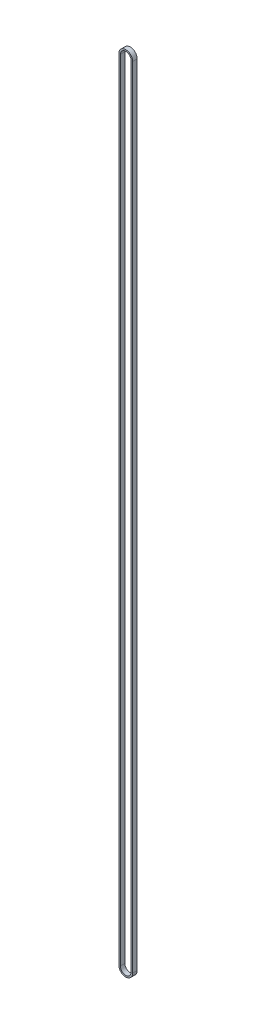
SolidWorks part; units mm, degrees
ref_plane "Front Plane" through (0, 0, 0) normal (0, 0, 1) x (1, 0, 0)
ref_plane "Top Plane" through (0, 0, 0) normal (0, 1, 0) x (1, 0, 0)
ref_plane "Right Plane" through (0, 0, 0) normal (1, 0, 0) x (0, 0, -1)
sketch "Sketch2" plane through (0, 0, 0) normal (0, 0, 1) x (1, 0, 0)
  line L0 (0, 0) -> (1, 0) construction
  line L1 (0, 0) -> (0, 1) construction
  line L2 (7.11, 0) -> (7.11, -1041)
  line L3 (-7.11, -1041) -> (-7.11, 0)
  arc A0 (-7.11, 0) -> (7.11, 0) centre (0, 0) cw
  arc A1 (7.11, -1041) -> (-7.11, -1041) centre (0, -1041) cw
extrude "Extrude-Thin1" add sketch "Sketch2" along normal mid plane 6 thin thin type one direction wall 2
